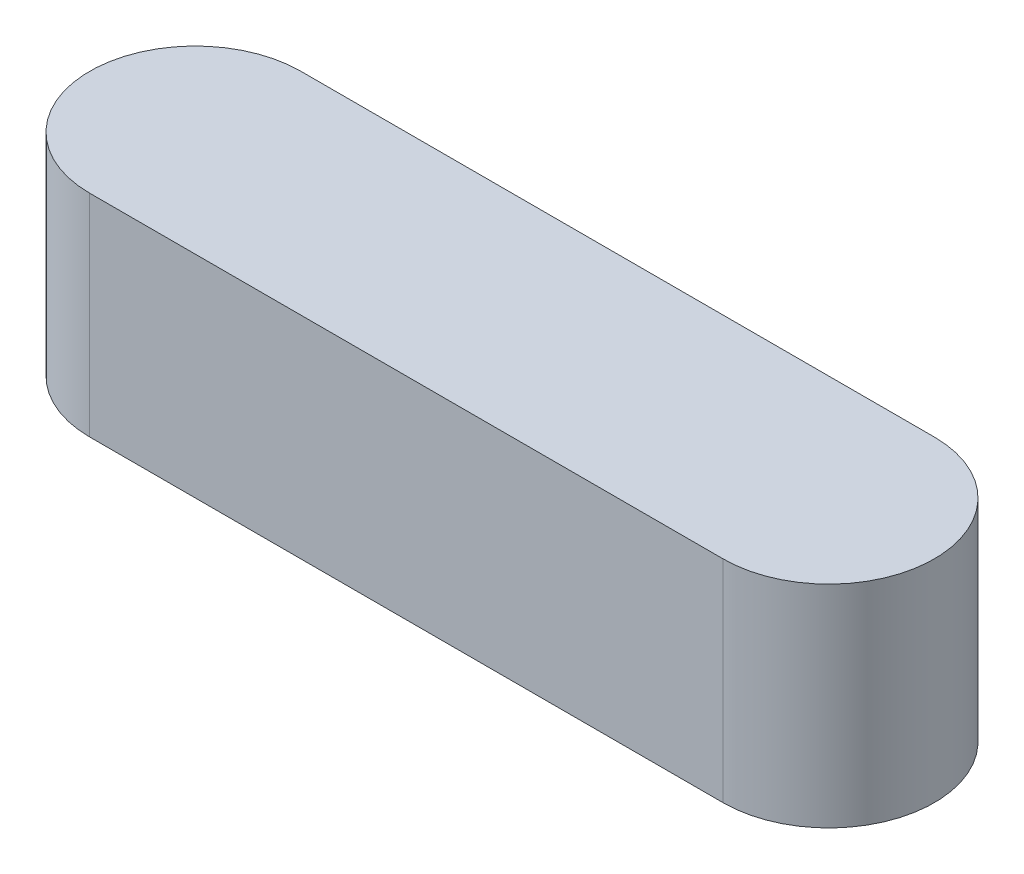
SolidWorks part; units mm, degrees
material "AISI 1020"
ref_plane "前视基准面" through (0, 0, 0) normal (0, 0, 1) x (1, 0, 0)
ref_plane "上视基准面" through (0, 0, 0) normal (0, 1, 0) x (1, 0, 0)
ref_plane "右视基准面" through (0, 0, 0) normal (1, 0, 0) x (0, 0, -1)
sketch "草图1" plane through (0, 0, 0) normal (0, 1, 0) x (1, 0, 0)
  line L0 (0, 0) -> (9, 0) construction
  line L1 (0, 1.5) -> (9, 1.5)
  line L2 (0, -1.5) -> (9, -1.5)
  arc A0 (0, 1.5) -> (0, -1.5) centre (0, 0) ccw
  arc A1 (9, -1.5) -> (9, 1.5) centre (9, 0) ccw
  point P3 (4.5, 0)
  dimension "D1" = 1.5
  dimension "D2" = 9
extrude "凸台-拉伸1" add sketch "草图1" along normal blind 3
move or copy body "实体-移动/复制1" [suppressed] bodies to move or copy 106
